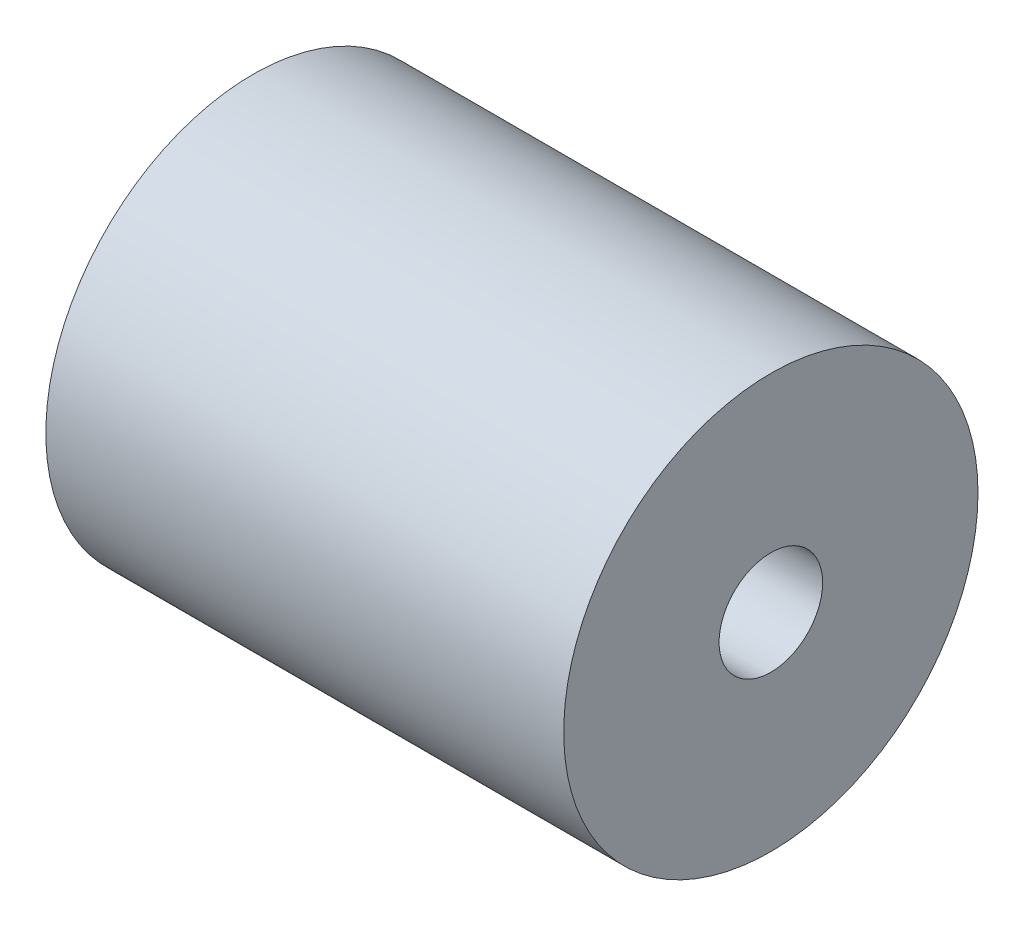
SolidWorks part; units mm, degrees
ref_plane "Front Plane" through (0, 0, 0) normal (0, 0, 1) x (1, 0, 0)
ref_plane "Top Plane" through (0, 0, 0) normal (0, 1, 0) x (1, 0, 0)
ref_plane "Right Plane" through (0, 0, 0) normal (1, 0, 0) x (0, 0, -1)
sketch "Sketch1" plane through (0, 0, 0) normal (1, 0, 0) x (0, 0, -1)
  circle A0 centre (0, 0) radius 10
  dimension "D1" = 20
extrude "Boss-Extrude1" add sketch "Sketch1" along normal mid plane 25
sketch "Sketch2" plane through (12.5, 0, 0) normal (1, 0, 0) x (0, 0, -1)
  circle A0 centre (0, 0) radius 2.5
  dimension "D1" = 5
extrude "Cut-Extrude1" cut sketch "Sketch2" against normal blind 12.5
sketch "Sketch3" plane through (-12.5, 0, 0) normal (-1, 0, 0) x (0, 0, 1)
  circle A0 centre (0, 0) radius 4
  dimension "D1" = 8
extrude "Cut-Extrude2" cut sketch "Sketch3" against normal blind 12.5
